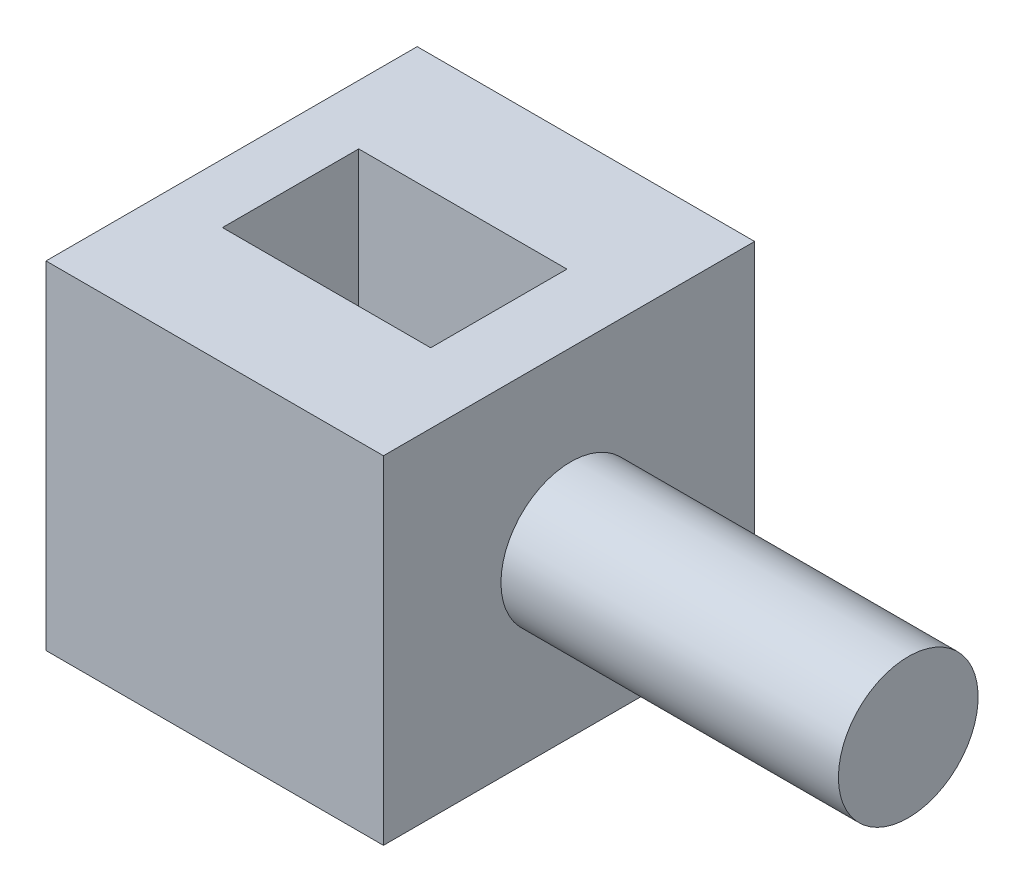
SolidWorks part; units mm, degrees
ref_plane "Front Plane" through (0, 0, 0) normal (0, 0, 1) x (1, 0, 0)
ref_plane "Top Plane" through (0, 0, 0) normal (0, 1, 0) x (1, 0, 0)
ref_plane "Right Plane" through (0, 0, 0) normal (1, 0, 0) x (0, 0, -1)
sketch "Sketch2" plane through (0, 0, 0) normal (0, 0, 1) x (1, 0, 0)
  line L1 (50, -50) -> (-50, -50)
  line L2 (50, -50) -> (50, 50)
  line L3 (50, 50) -> (-50, 50)
  line L4 (-50, -50) -> (-50, 50)
  line L5 (50, -50) -> (-50, 50) construction
  line L6 (50, 50) -> (-50, -50) construction
  point P0 (0, 0)
  dimension "D1" = 100
  dimension "D2" = 100
extrude "Boss-Extrude1" add sketch "Sketch2" against normal blind 100 and the other way blind 10
sketch "Sketch3" plane through (50, 0, 0) normal (1, 0, 0) x (0, 0, -1)
  circle A0 centre (45.5306, 0) radius 20.7046
extrude "Boss-Extrude2" add sketch "Sketch3" along normal blind 100
sketch "Sketch4" plane through (0, 50, 0) normal (0, 1, 0) x (1, 0, 0)
  line L1 (-32.4125, 65.0906) -> (29.2944, 65.0906)
  line L2 (-32.4125, 65.0906) -> (-32.4125, 24.7044)
  line L3 (-32.4125, 24.7044) -> (29.2944, 24.7044)
  line L4 (29.2944, 65.0906) -> (29.2944, 24.7044)
extrude "Cut-Extrude1" cut sketch "Sketch4" against normal through all
